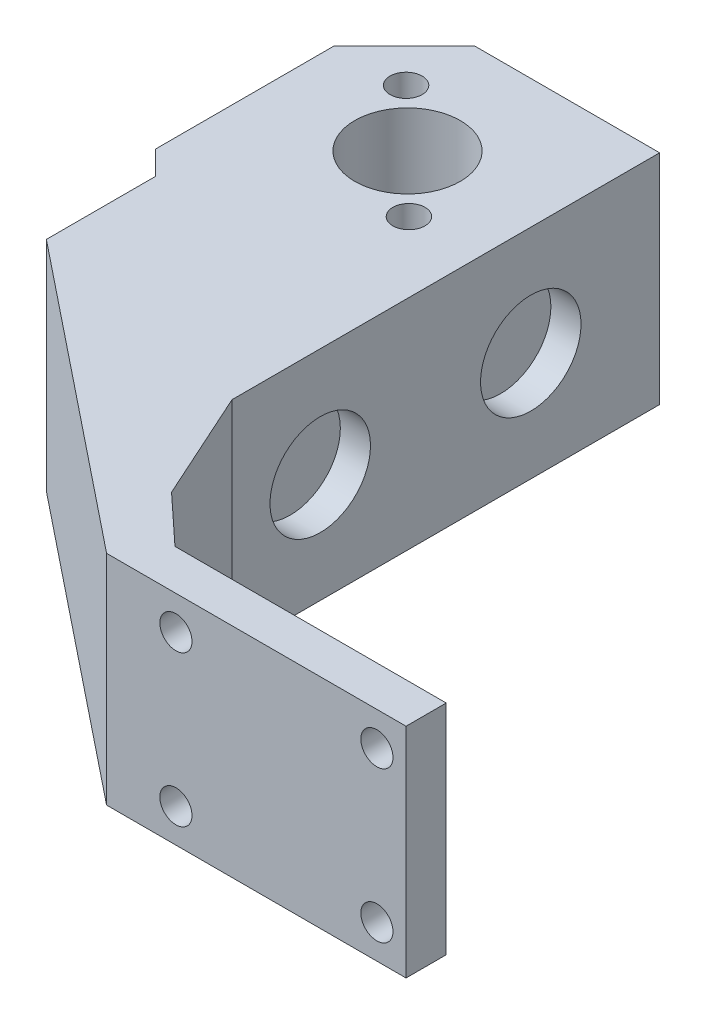
SolidWorks part; units mm, degrees
ref_plane "Přední rovina" through (0, 0, 0) normal (0, 0, 1) x (1, 0, 0)
ref_plane "Horní rovina" through (0, 0, 0) normal (0, 1, 0) x (1, 0, 0)
ref_plane "Pravá rovina" through (0, 0, 0) normal (1, 0, 0) x (0, 0, -1)
sketch "Skica1" plane through (0, 0, 0) normal (0, 0, 1) x (1, 0, 0)
  line L1 (16.212, -19.9414) -> (-9.588, -19.9414)
  line L2 (16.212, -19.9414) -> (16.212, 1.7586)
  line L3 (16.212, 1.7586) -> (-9.588, 1.7586)
  line L4 (-9.588, -19.9414) -> (-9.588, 1.7586)
  circle A0 centre (-6.688, -1.5914) radius 1.6
  circle A1 centre (13.312, -1.5914) radius 1.6
  circle A2 centre (13.312, -16.5914) radius 1.6
  circle A3 centre (-6.688, -16.5914) radius 1.6
  dimension "D1" = 3.2
  dimension "D2" = 2
  dimension "D3" = 2
extrude "Přidat vysunutím1" add sketch "Skica1" along normal blind 4
sketch "Skica2" plane through (-9.588, 0, 0) normal (-1, 0, 0) x (0, 0, 1)
  line L1 (4, -19.9414) -> (0, -19.9414)
  line L2 (4, -19.9414) -> (4, 1.7586)
  line L3 (4, 1.7586) -> (0, 1.7586)
  line L4 (0, -19.9414) -> (0, 1.7586)
extrude "Přidat vysunutím2" add sketch "Skica2" along normal blind 4
sketch "Skica4" plane through (0, 1.7586, 0) normal (0, 1, 0) x (1, 0, 0)
  line L0 (-13.588, -4) -> (-13.588, 0)
  line L1 (-13.588, -4) -> (-43.6402, 20.0598)
  line L3 (-43.6402, 20.0598) -> (-43.6402, 24.0598)
  line L4 (-15.6228, 4.5002) -> (-20.5891, 15.4839)
  line L6 (-43.6402, 20.0598) -> (-43.6402, 30.9081)
  line L7 (-43.6402, 58.0377) -> (-22.6582, 58.0377)
  line L15 (-45.9944, 33.2623) -> (-45.9944, 58.0377)
  line L16 (-45.9944, 58.0377) -> (-20.5891, 58.0377)
  line L17 (-20.5891, 33.2623) -> (-20.5891, 58.0377)
  line L19 (-41.1669, 53.3299) -> (-25.4166, 37.9701) construction
  line L20 (-41.1669, 37.9701) -> (-25.4166, 53.3299) construction
  line L21 (-45.9944, 33.2623) -> (-43.6402, 30.9081)
  line L22 (-20.5891, 33.2623) -> (-20.5891, 15.4839)
  line L23 (-10.7834, 0) -> (-15.6228, 4.5002)
  line L24 (16.212, 0) -> (-13.588, 0) construction
  line L25 (-10.7834, 0) -> (-13.588, 0)
  circle A0 centre (-33.2918, 45.65) radius 5.25
  circle A1 centre (-33.2918, 45.65) radius 11 construction
  circle A2 centre (-33.2918, 45.65) radius 8 construction
  circle A3 centre (-39.0192, 51.2354) radius 1.6
  circle A4 centre (-27.5643, 40.0646) radius 1.6
  point P34 (-33.2918, 45.65)
  dimension "D1" = 10.5
  dimension "D2" = 22
  dimension "D3" = 16
  dimension "D4" = 3.2
  dimension "D5" = 2
extrude "Přidat vysunutím3" add sketch "Skica4" against normal up to surface (21.7 mm away)
chamfer "Zkosení1" distance 7 angle 45 1 edges at (-45.9944, -9.0914, -58.0377)
sketch "Skica5" plane through (-20.5891, 0, 0) normal (1, 0, 0) x (0, 0, -1)
  line L0 (58.0377, -9.0914) -> (15.4839, -9.0914) construction
  line L1 (58.0377, -19.9414) -> (58.0377, 1.7586) construction
  line L2 (15.4839, -19.9414) -> (15.4839, 1.7586) construction
  circle A0 centre (24.2637, -9.0914) radius 5
  circle A1 centre (45.2162, -9.0914) radius 5
  dimension "D1" = 10
extrude "Odebrat vysunutím1" cut sketch "Skica5" against normal blind 3
